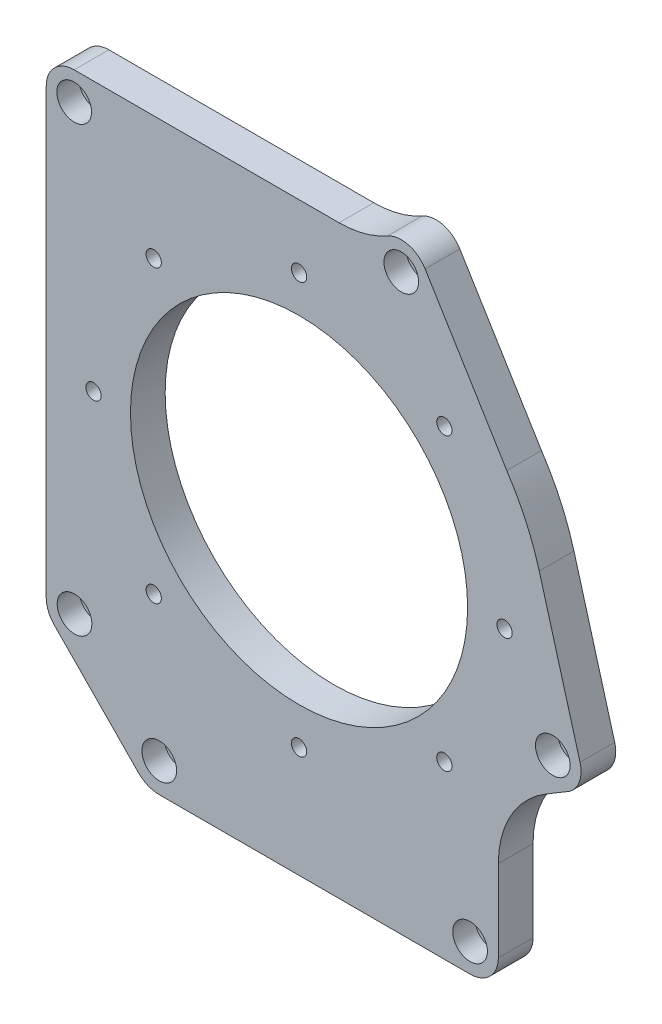
SolidWorks part; units mm, degrees
material "6061-T6 (SS)"
ref_plane "Front Plane" through (0, 0, 0) normal (0, 0, 1) x (1, 0, 0)
ref_plane "Top Plane" through (0, 0, 0) normal (0, 1, 0) x (1, 0, 0)
ref_plane "Right Plane" through (0, 0, 0) normal (1, 0, 0) x (0, 0, -1)
sketch "Sketch1" plane through (0, 0, 0) normal (0, 0, 1) x (1, 0, 0)
  line L4 (103.4521, -149.548) -> (103.4521, -78.3571)
  line L5 (145.8484, -40.455) -> (124.6867, 34.9424)
  line L6 (65.4501, 141.1203) -> (107.8436, 71.6445)
  line L9 (45.3968, 145.8694) -> (35.2457, 139.5357)
  line L13 (-116.7133, 139.5357) -> (35.2457, 139.5357)
  line L14 (-131.2133, 125.0357) -> (-131.2133, -104.9643)
  line L15 (103.4521, -78.3571) -> (140.5467, -56.1412)
  line L16 (88.6822, -164.2194) -> (-72.5383, -164.2194)
  line L18 (-83.4218, -159.6518) -> (-127.0122, -115.2417)
  arc A2 (-116.7133, 139.5357) -> (-131.2133, 125.0357) centre (-116.7133, 125.0357) ccw
  circle A3 centre (-116.7133, 125.0357) radius 3.5 construction
  arc A6 (65.4501, 141.1203) -> (45.3968, 145.8694) centre (53.0725, 133.5676) ccw
  circle A7 centre (-76.5534, 103.7539) radius 2.5 construction
  circle A10 centre (-116.5415, -104.9643) radius 3.5 construction
  circle A13 centre (-72.5383, -148.9692) radius 3.5 construction
  arc A15 (88.6822, -164.2194) -> (103.4521, -149.548) centre (88.7803, -149.548) ccw
  arc A17 (140.5467, -56.1412) -> (145.8484, -40.455) centre (131.7224, -44.4197) ccw
  circle A18 centre (59.1026, -114.9804) radius 2.5 construction
  circle A23 centre (88.7803, -149.548) radius 3.5 construction
  arc A26 (-83.4218, -159.6518) -> (-72.5383, -164.2194) centre (-72.5383, -148.9692) ccw
  circle A27 centre (131.7224, -44.4197) radius 3.5 construction
  arc A30 (124.6867, 34.9424) -> (107.8436, 71.6445) centre (-0.017, -0.0702) ccw
  circle A31 centre (53.0725, 133.5676) radius 3.5 construction
  arc A33 (-131.2133, -104.9643) -> (-127.0122, -115.2417) centre (-116.5415, -104.9643) ccw
  dimension "D1" = 14.5
  dimension "D2" = 7
  dimension "D3" = 5
  dimension "D4" = 143.7969
  dimension "D5" = 171.0833
  dimension "D6" = 156.7824
  dimension "D7" = 165.6208
  dimension "D8" = 173.8637
  dimension "D9" = 131.7395
  dimension "D10" = 129.2265
  dimension "D11" = 128.9855
  dimension "D12" = 229.9999
  dimension "D13" = 62.2312
  dimension "D14" = 161.3186
  dimension "D15" = 113.5605
  dimension "D16" = 194.59
  dimension "D17" = 169.7858
  dimension "D18" = 257.3854
extrude "Boss-Extrude1" add sketch "Sketch1" along normal blind 18.0086
fillet "Fillet2" radius 50.8 2 edges at (35.2457, 139.5357, 9.0043) (103.4521, -78.3571, 9.0043)
hole_wizard "CBORE for M10 SHCS7" positions "Sketch62" profile "Sketch63" counterbore size "M10" standard "ANSI Metric" end condition through all
sketch "Sketch62" plane through (0, 0, 18.0086) normal (0, 0, 1) x (1, 0, 0)
  point P0 (-116.7133, 125.0357)
  point P3 (-116.5415, -104.9643)
  point P7 (-72.5383, -148.9692)
  point P10 (53.0725, 133.5676)
  point P13 (131.7224, -44.4197)
  point P16 (88.7803, -149.548)
sketch "Sketch63" plane through (-116.7133, 125.0357, 18.0086) normal (1, 0, 0) x (0, -1, 0)
  line L0 (0, 0) -> (0, 18.0086)
  line L1 (0, 18.0086) -> (5.25, 18.0086)
  line L3 (5.25, 18.0086) -> (5.25, 11.5)
  line L4 (5.25, 11.5) -> (9, 11.5)
  line L5 (9, 11.5) -> (9, 0)
  line L7 (9, 0) -> (0, 0)
  line L11 (0, -6.35) -> (0, 107.95) construction
  dimension "Thru Hole Dia." = 10.5
  dimension "Thru Hole Depth" = 18.0086
  dimension "C'Bore Dia." = 18
  dimension "C'Bore Depth" = 11.5
hole_wizard "Ø10.0mm Dowel Hole3" positions "Sketch72" profile "Sketch73" hole size "Ø10.0" standard "ANSI Metric"
sketch "Sketch72" plane through (0, 0, 0) normal (0, 0, -1) x (-1, 0, 0)
  point P0 (76.5534, 103.7539)
  point P3 (-59.1026, -114.9804)
sketch "Sketch73" plane through (-76.5534, 103.7539, 0) normal (1, 0, 0) x (0, 1, 0)
  line L0 (0, 0) -> (0, 13.0043)
  line L1 (0, 13.0043) -> (5, 10)
  line L2 (5, 10) -> (5, 0)
  line L5 (5, 0) -> (0, 0)
  line L10 (0, 13.0043) -> (-5, 10) construction
  line L11 (0, -6.35) -> (0, 107.95) construction
  dimension "Hole Dia." = 10
  dimension "Hole Depth" = 10
  dimension "Drill Angle" = 118
sketch "Sketch79" plane through (0, 0, 18.0086) normal (0, 0, 1) x (1, 0, 0)
  circle A0 centre (0, 0) radius 87.5
  dimension "D1" = 175
extrude "Cut-Extrude3" cut sketch "Sketch79" against normal through all
sketch "Sketch84" plane through (0, 0, 18.0086) normal (0, 0, 1) x (1, 0, 0)
  line L0 (0, 0) -> (106.68, 0) construction
  line L1 (0, 0) -> (75.4342, -75.4342) construction
  circle A0 centre (0, 0) radius 106.68 construction
  circle A1 centre (106.68, 0) radius 4.8667
  circle A2 centre (75.4342, -75.4342) radius 4.8667
  circle A3 centre (-75.4342, -75.4342) radius 4.8667
  circle A4 centre (-75.4342, 75.4342) radius 4.8667
  circle A5 centre (75.4342, 75.4342) radius 4.8667
  point P15 (0, 0)
  dimension "D1" = 213.36
  dimension "D2" = 45
  dimension "D3" = 4
hole_wizard "3/8-16 Tapped Hole3" positions "Sketch85" profile "Sketch86" tap size "3/8-16" standard "ANSI Inch" end condition through all
sketch "Sketch85" plane through (0, 0, 18.0086) normal (0, 0, 1) x (1, 0, 0)
  line L0 (0, 0) -> (106.68, 0) construction
  line L1 (0, 0) -> (0, -106.68) construction
  line L3 (0, 0) -> (0, 106.68) construction
  line L5 (0, 0) -> (-106.68, 0) construction
  circle A0 centre (0, 0) radius 106.68 construction
  point P0 (75.4342, -75.4342)
  point P3 (75.4342, 75.4342)
  point P6 (-75.4342, 75.4342)
  point P9 (-75.4342, -75.4342)
  point P18 (106.68, 0)
  point P26 (0, -106.68)
  point P31 (0, 106.68)
  point P36 (-106.68, 0)
sketch "Sketch86" plane through (75.4342, -75.4342, 18.0086) normal (1, 0, 0) x (0, -1, 0)
  line L0 (0, 0) -> (0, 18.0086)
  line L1 (0, 18.0086) -> (3.9687, 18.0086)
  line L2 (3.9687, 18.0086) -> (3.9687, 0)
  line L5 (3.9687, 0) -> (0, 0)
  line L11 (0, -6.35) -> (0, 107.95) construction
  dimension "Thread Major Dia." = 7.9375
  dimension "Thru Tap Drill Depth" = 18.0086
equation "\"117.300x2\"=117.3"
